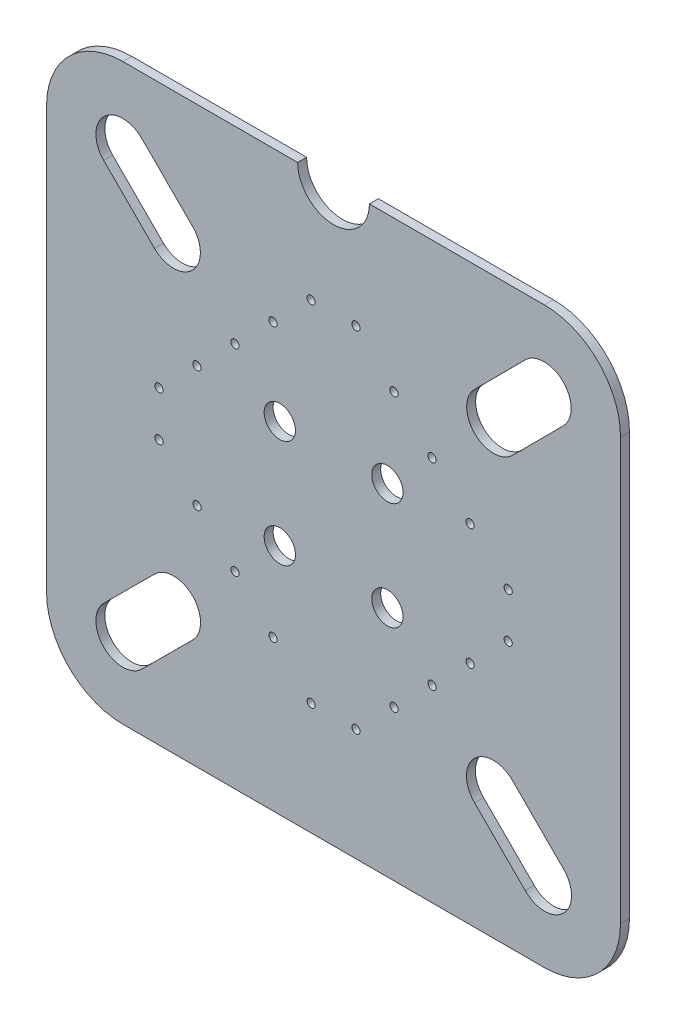
SolidWorks part; units mm, degrees
material "Plain Carbon Steel"
ref_plane "Front Plane" through (0, 0, 0) normal (0, 0, 1) x (1, 0, 0)
ref_plane "Top Plane" through (0, 0, 0) normal (0, 1, 0) x (1, 0, 0)
ref_plane "Right Plane" through (0, 0, 0) normal (1, 0, 0) x (0, 0, -1)
sketch "Model" plane through (0, 0, 0) normal (0, 0, 1) x (1, 0, 0)
  line L0 (9.0666, 140.0299) -> (45.0494, 175.8729)
  line L1 (18.0908, 202.8251) -> (-17.8928, 166.9845)
  line L2 (307.5157, 166.9845) -> (271.6729, 202.8251)
  line L3 (244.7252, 175.8729) -> (280.5657, 140.0299)
  line L4 (-17.8928, 438.4834) -> (18.0908, 402.5004)
  line L5 (45.0494, 429.4542) -> (9.0666, 465.438)
  line L6 (280.5657, 465.438) -> (244.7252, 429.4542)
  line L7 (271.6729, 402.5004) -> (307.5157, 438.4834)
  line L8 (119.4141, 505.9356) -> (-4.3404, 505.9356)
  line L9 (-58.3859, 451.89) -> (-58.3859, 153.44)
  line L10 (-4.3404, 99.5356) -> (294.1097, 99.5356)
  line L11 (348.014, 153.44) -> (348.014, 451.89)
  line L12 (294.1097, 505.9356) -> (170.2141, 505.9356)
  circle A0 centre (128.9391, 426.3842) radius 2.893
  circle A1 centre (75.047, 372.5053) radius 2.9058
  circle A2 centre (21.2392, 318.617) radius 2.8617
  circle A3 centre (48.2114, 259.9181) radius 2.906
  circle A4 centre (101.9868, 206.0392) radius 2.893
  circle A5 centre (160.6879, 179.0161) radius 2.8935
  circle A6 centre (214.5935, 232.9209) radius 2.893
  circle A7 centre (268.498, 286.8253) radius 2.893
  circle A8 centre (241.5028, 345.5127) radius 2.9358
  circle A9 centre (187.6413, 399.3614) radius 2.893
  circle A10 centre (160.6891, 426.3136) radius 2.893
  circle A11 centre (214.5506, 372.4649) radius 2.9357
  circle A12 centre (268.4991, 318.6461) radius 2.8935
  circle A13 centre (241.5457, 259.8731) radius 2.893
  circle A14 centre (187.6401, 205.9684) radius 2.8935
  circle A15 centre (128.9391, 179.087) radius 2.893
  circle A16 centre (75.0665, 232.9497) radius 2.8617
  circle A17 centre (21.2592, 286.8703) radius 2.906
  circle A18 centre (48.0948, 345.5531) radius 2.9058
  circle A19 centre (101.9868, 399.432) radius 2.893
  circle A20 centre (106.7747, 264.5835) radius 11.0873
  circle A21 centre (106.7747, 340.7835) radius 11.0873
  circle A22 centre (182.9747, 340.7835) radius 11.0873
  circle A23 centre (182.9747, 264.5835) radius 11.0873
  arc A24 (45.0494, 175.8729) -> (18.0908, 202.8251) centre (31.598, 189.3769) ccw
  arc A25 (-17.8928, 166.9845) -> (9.0666, 140.0299) centre (-4.3857, 153.5347) ccw
  arc A26 (271.6729, 202.8251) -> (244.7252, 175.8729) centre (257.9958, 189.5522) ccw
  arc A27 (280.5657, 140.0299) -> (307.5157, 166.9845) centre (294.2928, 153.2551) ccw
  arc A28 (18.0908, 402.5004) -> (45.0494, 429.4542) centre (31.4658, 416.0816) ccw
  arc A29 (9.0666, 465.438) -> (-17.8928, 438.4834) centre (-4.3857, 451.9332) ccw
  arc A30 (244.7252, 429.4542) -> (271.6729, 402.5004) centre (258.1712, 415.9494) ccw
  arc A31 (307.5157, 438.4834) -> (280.5657, 465.438) centre (294.0132, 451.9332) ccw
  arc A32 (119.4141, 505.9356) -> (170.2141, 505.9356) centre (144.8141, 505.9032) ccw
  arc A33 (-4.3404, 505.9356) -> (-58.3859, 451.89) centre (-4.3028, 451.8524) ccw
  arc A34 (-58.3859, 153.44) -> (-4.3404, 99.5356) centre (-4.3027, 153.6191) ccw
  arc A35 (294.1097, 99.5356) -> (348.014, 153.44) centre (294.1624, 153.3872) ccw
  arc A36 (348.014, 451.89) -> (294.1097, 505.9356) centre (294.1621, 452.0833) ccw
  dimension "D1" = 22.1745
  dimension "D2" = 5.786
  dimension "D3" = 5.8715
  dimension "D4" = 5.8715
  dimension "D5" = 5.7235
  dimension "D6" = 5.7233
  dimension "D7" = 5.7871
  dimension "D8" = 5.812
  dimension "D9" = 5.8116
  dimension "D10" = 5.7871
  dimension "D11" = 19.0604
  dimension "D12" = 19.0615
  dimension "D13" = 19.0586
  dimension "D14" = 19.0571
  dimension "D15" = 19.0582
  dimension "D16" = 25.4
  dimension "D17" = 54.0831
  dimension "D18" = 54.0835
  dimension "D19" = 53.8517
  dimension "D20" = 53.8523
  dimension "D21" = 9.0666
  dimension "D22" = 18.0908
  dimension "D23" = 21.2392
  dimension "D24" = 21.2592
  dimension "D25" = 31.4658
  dimension "D26" = 31.598
  dimension "D27" = 119.4141
  dimension "D28" = 48.0948
  dimension "D29" = 48.2114
  dimension "D30" = 75.047
  dimension "D31" = 75.0665
  dimension "D32" = 101.9868
  dimension "D33" = 106.7747
  dimension "D34" = 144.8141
  dimension "D35" = 128.9391
  dimension "D36" = 294.1097
  dimension "D37" = 160.6879
  dimension "D38" = 160.6891
  dimension "D39" = 294.1621
  dimension "D40" = 182.9747
  dimension "D41" = 187.6401
  dimension "D42" = 187.6413
  dimension "D43" = 214.5506
  dimension "D44" = 214.5935
  dimension "D45" = 241.5028
  dimension "D46" = 241.5457
  dimension "D47" = 294.1624
  dimension "D48" = 348.014
  dimension "D49" = 4.3027
  dimension "D50" = 268.498
  dimension "D51" = 268.4991
  dimension "D52" = 4.3028
  dimension "D53" = 99.5356
  dimension "D54" = 140.0299
  dimension "D55" = 153.44
  dimension "D62" = 179.0161
  dimension "D63" = 179.087
  dimension "D67" = 205.9684
  dimension "D68" = 206.0392
  dimension "D69" = 232.9209
  dimension "D70" = 232.9497
  dimension "D71" = 259.8731
  dimension "D72" = 259.9181
  dimension "D73" = 264.5835
  dimension "D74" = 286.8253
  dimension "D75" = 286.8703
  dimension "D76" = 318.617
  dimension "D77" = 318.6461
  dimension "D78" = 340.7835
  dimension "D79" = 345.5127
  dimension "D80" = 345.5531
  dimension "D81" = 372.4649
  dimension "D82" = 372.5053
  dimension "D83" = 399.3614
  dimension "D84" = 399.432
  dimension "D88" = 426.3136
  dimension "D89" = 426.3842
extrude "Boss-Extrude1" add sketch "Model" along normal blind 6.35
sketch "Sketch2" plane through (0, 0, 0) normal (0, 0, -1) x (-1, 0, 0)
  line L0 (58.3859, 451.89) -> (58.3859, 153.44) construction
  line L1 (4.3404, 99.5356) -> (-294.1097, 99.5356) construction
  text T0 "9005538"
  point P1 (-156.0433, 111.7998)
  dimension "D1" = 207.1937
  dimension "D2" = 33.7157
extrude "Cut-Extrude1" cut sketch "Sketch2" against normal blind 2.54
